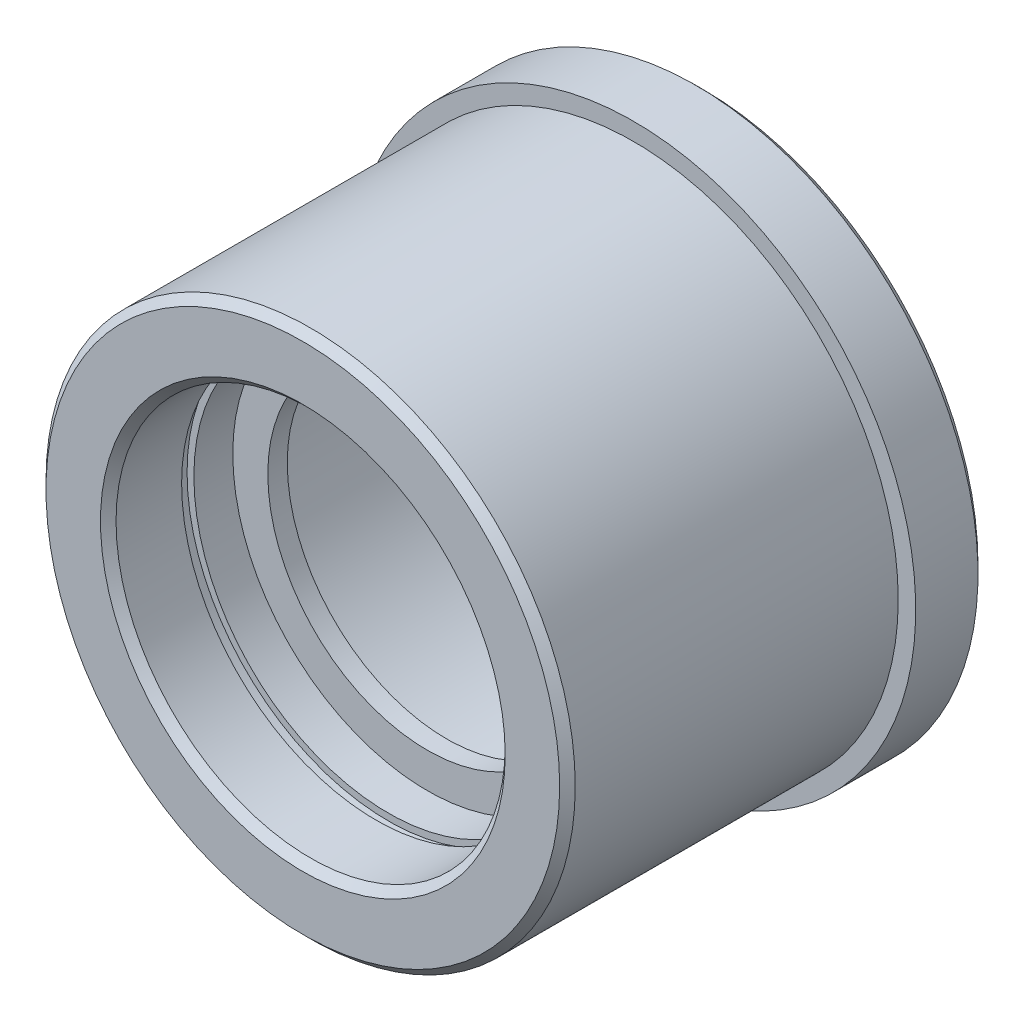
SolidWorks part; units mm, degrees
material "08Х18Н10 ГОСТ 4543-71"
ref_plane "Спереди" through (0, 0, 0) normal (0, 0, 1) x (1, 0, 0)
ref_plane "Сверху" through (0, 0, 0) normal (0, 1, 0) x (1, 0, 0)
ref_plane "Справа" through (0, 0, 0) normal (1, 0, 0) x (0, 0, -1)
sketch "Эскиз1" plane through (0, 0, 0) normal (1, 0, 0) x (0, 0, -1)
  line L0 (-84.15, 50) -> (-103, 50)
  line L1 (-103, 68) -> (-18, 68)
  line L2 (0, 72.5) -> (0, 60)
  line L3 (0, 60) -> (-9.85, 60)
  line L6 (-71, 41) -> (-71, 50)
  line L7 (-71, 50) -> (-81, 50)
  line L9 (0, 0) -> (-112.841, 0) construction
  line L10 (-71, 41) -> (-66, 41)
  line L11 (-66, 41) -> (-66, 50)
  line L12 (-66, 50) -> (-63, 50)
  line L13 (-63, 50) -> (-63, 60)
  line L15 (-103, 50) -> (-103, 68)
  line L19 (-84.15, 50) -> (-84.15, 51.75)
  line L20 (-84.15, 51.75) -> (-81, 51.75)
  line L21 (-81, 51.75) -> (-81, 50)
  line L22 (-14, 60) -> (-14, 62)
  line L23 (-14, 62) -> (-9.85, 62)
  line L24 (-9.85, 62) -> (-9.85, 60)
  line L25 (-14, 60) -> (-63, 60)
  line L26 (0, 72.5) -> (-18, 72.5)
  line L27 (-18, 72.5) -> (-18, 68)
  dimension "D2" = 100
  dimension "D3" = 82
  dimension "D4" = 120
  dimension "D5" = 10
  dimension "D6" = 5
  dimension "D7" = 18
  dimension "63" = 63
  dimension "D8" = 145
  dimension "D9" = 3
  dimension "D12" = 136
  dimension "D13" = 9.85
  dimension "D14" = 4.15
  dimension "D15" = 124
  dimension "D16" = 18.85
  dimension "D17" = 3.15
  dimension "D18" = 103.5
revolve "Повернуть1" add sketch "Эскиз1" angle 360 about L9
chamfer "Фаска2" distance 2 angle 45 4 edges at (-60, 0, 0) (-50, 0, 103) (-68, 0, 103) (-72.5, 0, 0)
